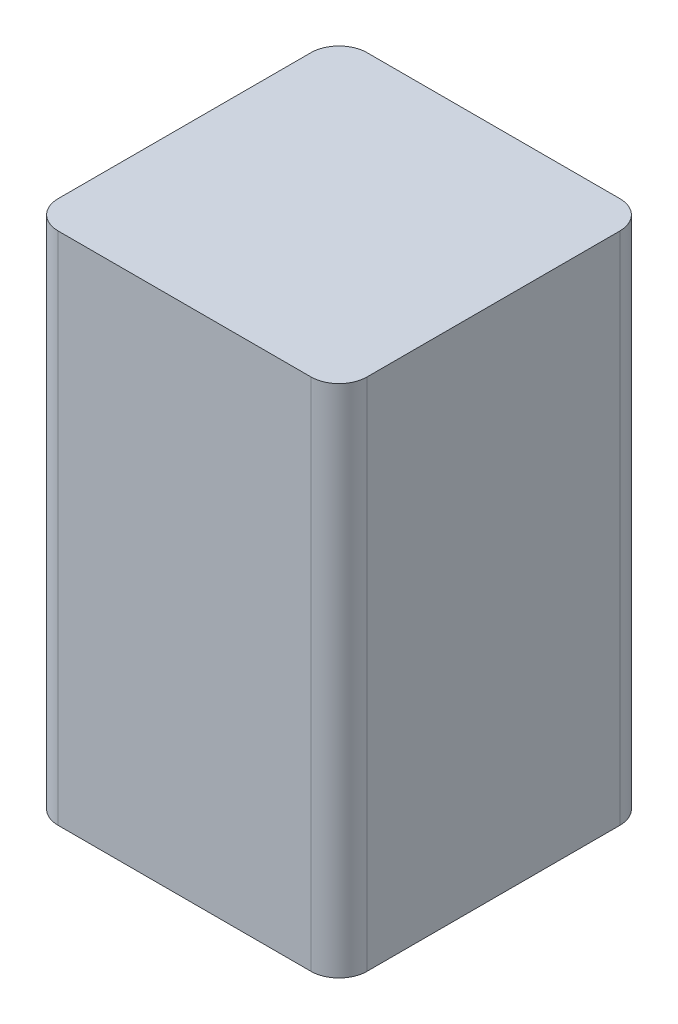
SolidWorks part; units mm, degrees
ref_plane "前视基准面" through (0, 0, 0) normal (0, 0, 1) x (1, 0, 0)
ref_plane "上视基准面" through (0, 0, 0) normal (0, 1, 0) x (1, 0, 0)
ref_plane "右视基准面" through (0, 0, 0) normal (1, 0, 0) x (0, 0, -1)
sketch "草图1" plane through (0, 0, 0) normal (0, 1, 0) x (1, 0, 0)
  line L1 (-16.5, 16.5) -> (16.5, 16.5)
  line L2 (-16.5, 16.5) -> (-16.5, -16.5)
  line L3 (-16.5, -16.5) -> (16.5, -16.5)
  line L4 (16.5, 16.5) -> (16.5, -16.5)
  line L5 (-16.5, 16.5) -> (16.5, -16.5) construction
  line L6 (-16.5, -16.5) -> (16.5, 16.5) construction
  point P0 (0, 0)
  dimension "D1" = 33
  dimension "D2" = 33
extrude "凸台-拉伸1" add sketch "草图1" along normal blind 55
fillet "圆角1" radius 3 4 edges at (-16.5, 27.5, -16.5) (16.5, 27.5, -16.5) (16.5, 27.5, 16.5) (-16.5, 27.5, 16.5)
